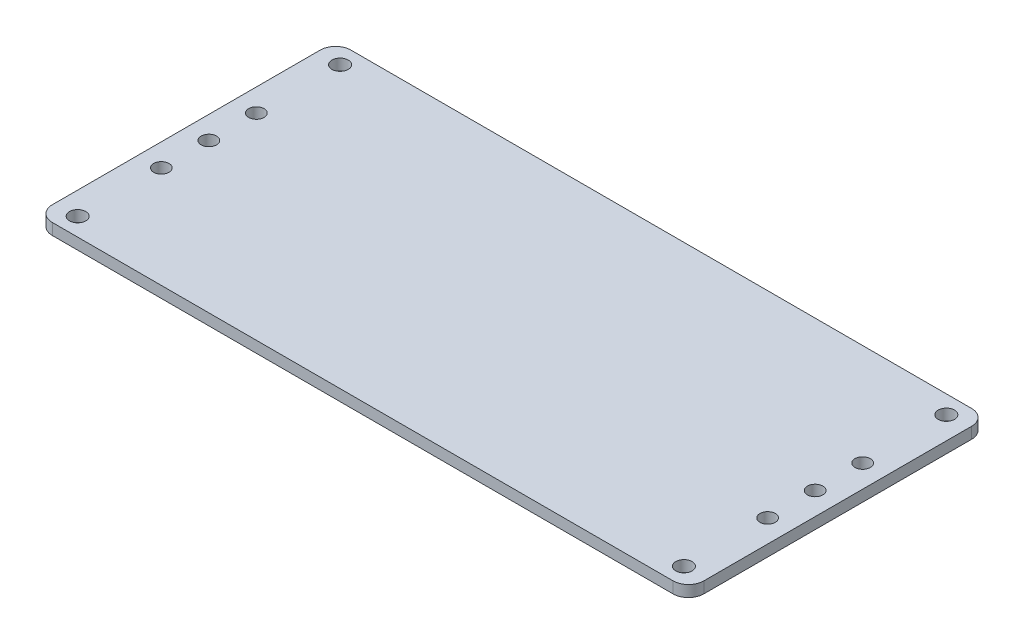
SolidWorks part; units mm, degrees
ref_plane "前视基准面" through (0, 0, 0) normal (0, 0, 1) x (1, 0, 0)
ref_plane "上视基准面" through (0, 0, 0) normal (0, 1, 0) x (1, 0, 0)
ref_plane "右视基准面" through (0, 0, 0) normal (1, 0, 0) x (0, 0, -1)
other "Configuration Table"
sketch "草图1" plane through (0, 0, 0) normal (0, 1, 0) x (1, 0, 0)
  line L0 (0, 0) -> (-67, 0) construction
  line L1 (-67, 0) -> (67, 0) construction
  line L2 (67, 0) -> (67, 10.5) construction
  line L3 (67, 10.5) -> (67, -10.5) construction
  line L4 (67, -10.5) -> (-67, -10.5) construction
  line L5 (-67, -10.5) -> (-67, 10.5) construction
  line L6 (-67, 10.5) -> (-67, 0) construction
  line L7 (-67, 0) -> (-67, 29) construction
  line L8 (-67, 29) -> (-67, 0) construction
  line L9 (-67, 0) -> (-67, -29) construction
  line L10 (-67, -29) -> (67, -29) construction
  line L11 (67, -29) -> (67, 0) construction
  line L12 (67, 0) -> (67, 29) construction
  line L14 (-72, 33) -> (72, 33)
  line L15 (-72, 33) -> (-72, -33)
  line L16 (-72, -33) -> (72, -33)
  line L17 (72, 33) -> (72, -33)
  line L18 (-72, 33) -> (72, -33) construction
  line L19 (-72, -33) -> (72, 33) construction
  circle A0 centre (-67, 29) radius 1.8
  circle A1 centre (67, 29) radius 1.8
  circle A2 centre (-67, -29) radius 1.8
  circle A3 centre (67, -29) radius 1.8
  circle A4 centre (-67, 0) radius 1.7
  circle A5 centre (-67, 10.5) radius 1.7
  circle A6 centre (-67, -10.5) radius 1.7
  circle A7 centre (67, 0) radius 1.7
  circle A8 centre (67, 10.5) radius 1.7
  circle A9 centre (67, -10.5) radius 1.7
  dimension "D10" = 3.6
  dimension "D11" = 3.6
  dimension "D12" = 3.6
  dimension "D13" = 3.6
  dimension "D14" = 3.4
  dimension "D15" = 3.4
  dimension "D16" = 3.4
  dimension "D17" = 3.4
  dimension "D18" = 3.4
  dimension "D19" = 3.4
  dimension "D1" = 67
  dimension "D2" = 134
  dimension "D3" = 10.5
  dimension "D4" = 21
  dimension "D5" = 134
  dimension "D6" = 21
  dimension "D7" = 29
  dimension "D8" = 29
  dimension "D9" = 29
  dimension "D20" = 66
  dimension "D21" = 144
extrude "凸台-拉伸1" add sketch "草图1" along normal blind 2.5
fillet "圆角1" radius 3.4 4 edges at (72, 1.25, 33) (72, 1.25, -33) (-72, 1.25, -33) (-72, 1.25, 33)
